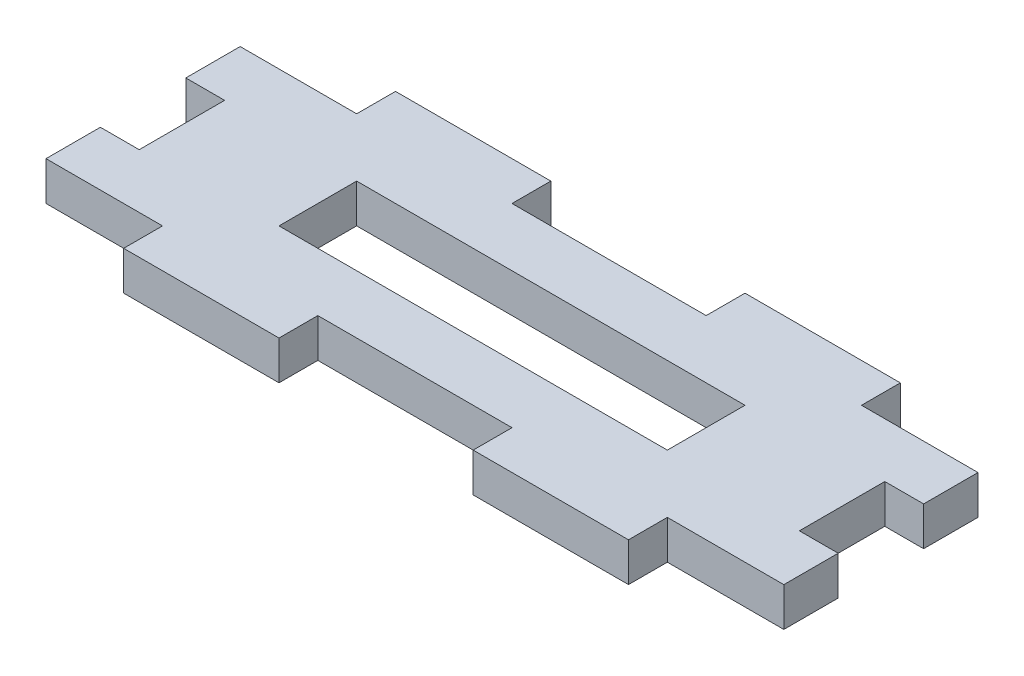
SolidWorks part; units mm, degrees
ref_plane "Front Plane" through (0, 0, 0) normal (0, 0, 1) x (1, 0, 0)
ref_plane "Top Plane" through (0, 0, 0) normal (0, 1, 0) x (1, 0, 0)
ref_plane "Right Plane" through (0, 0, 0) normal (1, 0, 0) x (0, 0, -1)
sketch "Sketch1" plane through (0, 0, 0) normal (0, 1, 0) x (1, 0, 0)
  line L0 (-12.5, 12.5) -> (12.5, 12.5)
  line L1 (-47.5, -12.5) -> (-32.5, -12.5)
  line L2 (-47.5, -12.5) -> (-47.5, -5.5)
  line L3 (-47.5, 12.5) -> (-32.5, 12.5)
  line L4 (47.5, -12.5) -> (47.5, -5.5)
  line L5 (-47.5, -12.5) -> (47.5, 12.5) construction
  line L6 (-47.5, 12.5) -> (47.5, -12.5) construction
  line L7 (-25, -5) -> (25, -5)
  line L8 (-25, -5) -> (-25, 5)
  line L9 (-25, 5) -> (25, 5)
  line L10 (25, -5) -> (25, 5)
  line L11 (-25, -5) -> (25, 5) construction
  line L12 (-25, 5) -> (25, -5) construction
  line L14 (-32.5, -12.5) -> (-32.5, -17.5)
  line L15 (-32.5, -17.5) -> (-12.5, -17.5)
  line L16 (-12.5, -12.5) -> (-12.5, -17.5)
  line L18 (12.5, -12.5) -> (12.5, -17.5)
  line L19 (12.5, -17.5) -> (32.5, -17.5)
  line L20 (32.5, -12.5) -> (32.5, -17.5)
  line L22 (-32.5, 12.5) -> (-32.5, 17.5)
  line L23 (-32.5, 17.5) -> (-12.5, 17.5)
  line L24 (-12.5, 12.5) -> (-12.5, 17.5)
  line L26 (12.5, 12.5) -> (12.5, 17.5)
  line L27 (12.5, 17.5) -> (32.5, 17.5)
  line L28 (32.5, 12.5) -> (32.5, 17.5)
  line L29 (32.5, 12.5) -> (47.5, 12.5)
  line L30 (32.5, -12.5) -> (47.5, -12.5)
  line L31 (-12.5, -12.5) -> (12.5, -12.5)
  line L32 (-47.5, 5.5) -> (-47.5, 12.5)
  line L33 (-47.5, 5.5) -> (-42.5, 5.5)
  line L35 (-47.5, -5.5) -> (-42.5, -5.5)
  line L36 (-42.5, 5.5) -> (-42.5, -5.5)
  line L37 (47.5, 5.5) -> (47.5, 12.5)
  line L38 (47.5, 5.5) -> (42.5, 5.5)
  line L40 (47.5, -5.5) -> (42.5, -5.5)
  line L41 (42.5, 5.5) -> (42.5, -5.5)
  point P0 (0, 0)
  point P6 (0, 0)
  dimension "D1" = 95
  dimension "D2" = 25
  dimension "D3" = 50
  dimension "D4" = 10
  dimension "D5" = 20
  dimension "D6" = 20
  dimension "D7" = 20
  dimension "D8" = 20
  dimension "D9" = 25
  dimension "D10" = 25
  dimension "D11" = 15
  dimension "D12" = 15
  dimension "D13" = 5
  dimension "D14" = 5
  dimension "D15" = 7
  dimension "D16" = 7
  dimension "D17" = 5
  dimension "D18" = 5
extrude "Boss-Extrude1" add sketch "Sketch1" along normal blind 5
